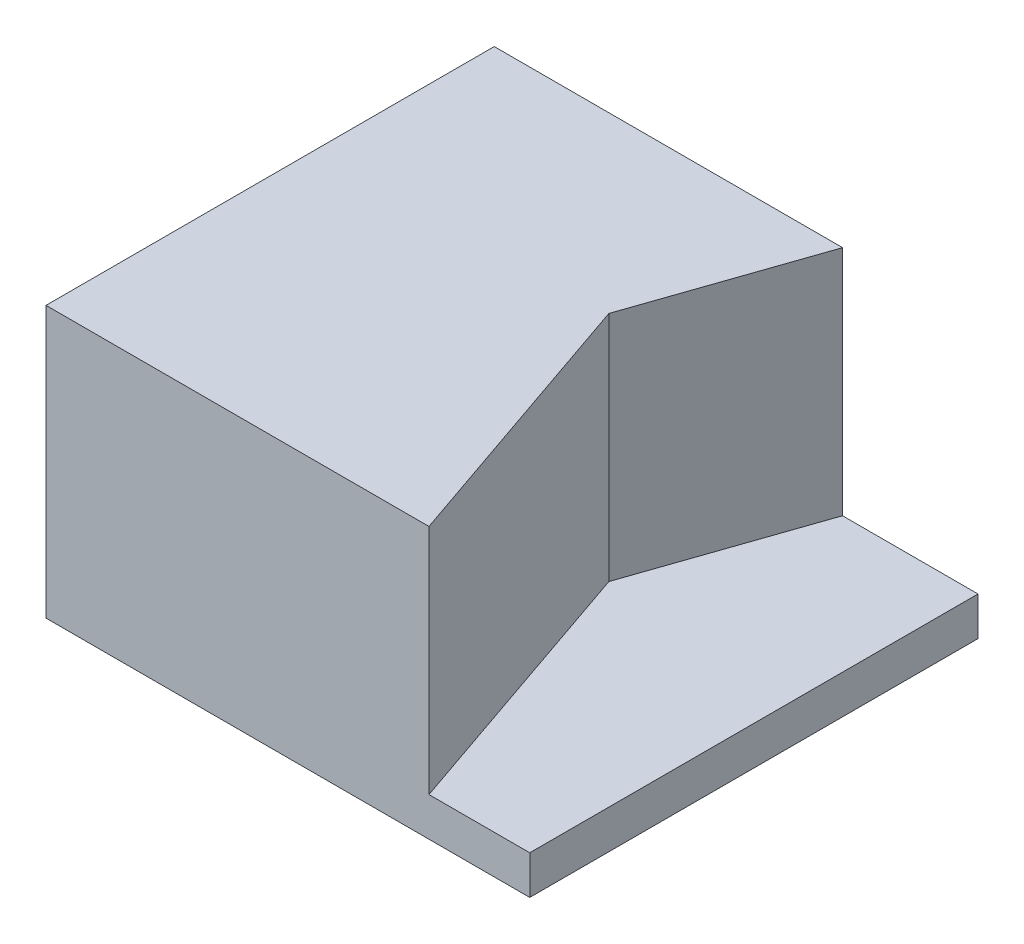
SolidWorks part; units mm, degrees
ref_plane "Front Plane" through (0, 0, 0) normal (0, 0, 1) x (1, 0, 0)
ref_plane "Top Plane" through (0, 0, 0) normal (0, 1, 0) x (1, 0, 0)
ref_plane "Right Plane" through (0, 0, 0) normal (1, 0, 0) x (0, 0, -1)
sketch "Sketch1" plane through (0, 0, 0) normal (0, 1, 0) x (1, 0, 0)
  line L0 (0, 0) -> (157.1192, 456.3073)
  line L1 (157.1192, 456.3073) -> (-757.2808, 456.3073)
  line L2 (-757.2808, 456.3073) -> (-757.2808, -720.4852)
  line L3 (-757.2808, -720.4852) -> (248.0829, -720.4852)
  line L4 (248.0829, -720.4852) -> (0, 0)
  line L5 (0, 456.3073) -> (0, -720.4852) construction
  dimension "D1" = 914.4
  dimension "D2" = 482.6
  dimension "D3" = 762
  dimension "D4" = 19
  dimension "D5" = 19
extrude "Boss-Extrude1" add sketch "Sketch1" along normal blind 609.6
sketch "Sketch2" plane through (0, 0, 0) normal (0, -1, 0) x (1, 0, 0)
  line L0 (157.1192, -456.3073) -> (-757.2808, -456.3073) construction
  line L1 (-757.2808, 720.4852) -> (512.7192, 720.4852)
  line L2 (-757.2808, 720.4852) -> (-757.2808, -456.3073)
  line L3 (-757.2808, -456.3073) -> (512.7192, -456.3073)
  line L4 (512.7192, 720.4852) -> (512.7192, -456.3073)
  dimension "D1" = 1270
extrude "Boss-Extrude2" add sketch "Sketch2" along normal blind 101.6
